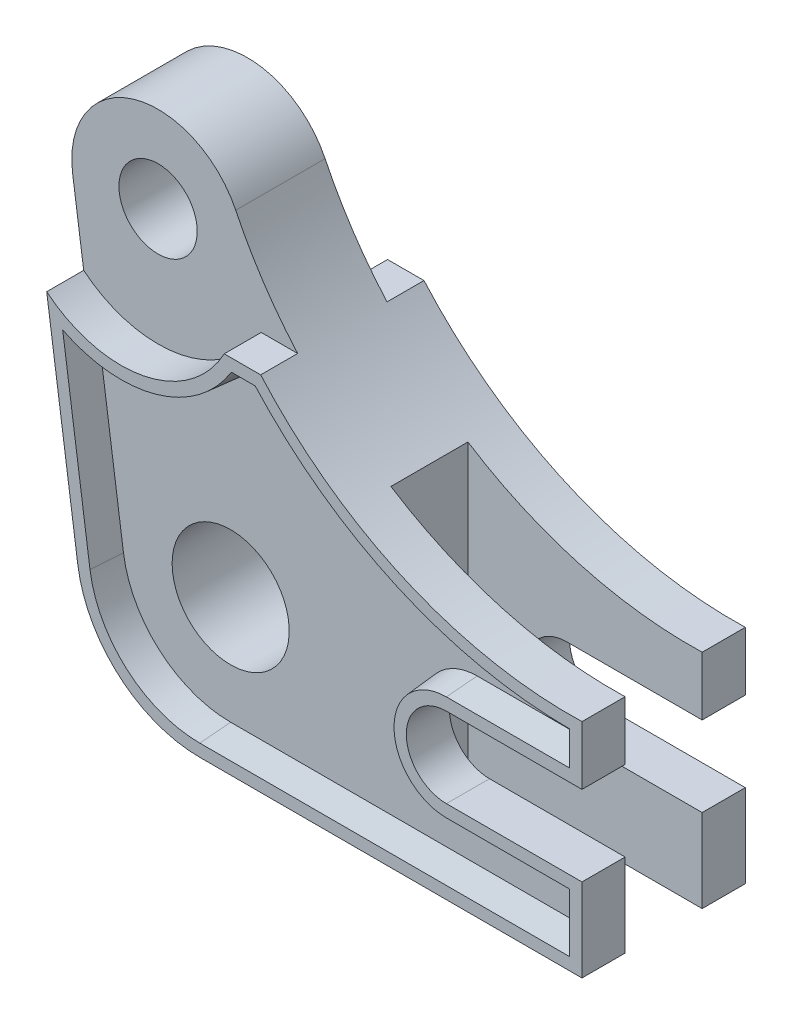
SolidWorks part; units mm, degrees
material "AISI 1020 Steel, Cold Rolled"
ref_plane "Front Plane" through (0, 0, 0) normal (0, 0, 1) x (1, 0, 0)
ref_plane "Top Plane" through (0, 0, 0) normal (0, 1, 0) x (1, 0, 0)
ref_plane "Right Plane" through (0, 0, 0) normal (1, 0, 0) x (0, 0, -1)
sketch "Sketch1" plane through (0, 0, 0) normal (0, 0, 1) x (1, 0, 0)
  line L0 (0, 0) -> (62, 0)
  line L1 (-19.8044, 17.21) -> (-26.64, 65.7309)
  line L2 (0, 20) -> (0, 45.9164) construction
  line L3 (0, 20) -> (-12.7769, 67.6839) construction
  line L4 (62, 0) -> (62, 36.0264)
  line L5 (40, 26.5) -> (62, 26.5)
  line L6 (40, 13.5) -> (62, 13.5)
  arc A0 (0, 0) -> (-19.8044, 17.21) centre (0, 20) cw
  arc A1 (-26.64, 65.7309) -> (-0.1776, 73.7879) centre (-12.7769, 67.6839) cw
  arc A2 (-0.1776, 73.7879) -> (62, 36.0264) centre (60.1188, 103) ccw
  circle A3 centre (0, 20) radius 9.5
  arc A4 (40, 26.5) -> (40, 13.5) centre (40, 20) ccw
  circle A5 centre (-12.7769, 67.6839) radius 6.35
  dimension "D2" = 20
  dimension "D4" = 14
  dimension "D8" = 19
  dimension "D9" = 13
  dimension "D12" = 12.7
  dimension "D6" = 134
  dimension "D1" = 62
  dimension "D3" = 49
  dimension "D5" = 15
  dimension "D10" = 22
  dimension "D11" = 20
  dimension "D7" = 103
extrude "Boss-Extrude1" add sketch "Sketch1" along normal blind 26.5 contours A4 L5 L4 A2 A1 L1 A0 L0 L6 A5 A3
sketch "Sketch2" plane through (0, 0, 0) normal (0, 1, 0) x (1, 0, 0)
  line L0 (62, -26.5) -> (62, 0) construction
  line L1 (24, -7) -> (62, -7)
  line L2 (24, -7) -> (24, -19.5)
  line L3 (24, -19.5) -> (62, -19.5)
  line L4 (62, -7) -> (62, -19.5)
  line L5 (62, 0) -> (-0.1776, 0) construction
  line L6 (-0.1776, -26.5) -> (62, -26.5) construction
  dimension "D1" = 7
  dimension "D2" = 7
  dimension "D3" = 38
extrude "Cut-Extrude1" cut sketch "Sketch2" along normal through all
sketch "Sketch3" plane through (0, 0, 26.5) normal (0, 0, 1) x (1, 0, 0)
  line L0 (3.9563, 58.6839) -> (9.8686, 58.6839)
  line L1 (-19.8044, 17.21) -> (-26.64, 65.7309) construction
  line L2 (-24.848, 53.0112) -> (-26.64, 65.7309)
  arc A0 (-24.848, 53.0112) -> (3.9563, 58.6839) centre (-12.7769, 67.6839) ccw
  arc A3 (-0.1776, 73.7879) -> (-26.64, 65.7309) centre (-12.7769, 67.6839) ccw construction
  arc A4 (-0.1776, 73.7879) -> (62, 36.0264) centre (60.1188, 103) ccw construction
  arc A5 (-0.1776, 73.7879) -> (9.8686, 58.6839) centre (60.1188, 103) ccw
  arc A6 (-0.1776, 73.7879) -> (-26.64, 65.7309) centre (-12.7769, 67.6839) ccw
  dimension "D1" = 38
  dimension "D2" = 9
extrude "Cut-Extrude3" cut sketch "Sketch3" against normal blind 6
sketch "Sketch6" plane through (0, 0, 0) normal (0, 0, -1) x (-1, 0, 0)
  line L0 (-9.8686, 58.6839) -> (-3.9563, 58.6839)
  line L1 (19.8044, 17.21) -> (26.64, 65.7309) construction
  line L2 (24.848, 53.0112) -> (26.64, 65.7309)
  arc A1 (-3.9563, 58.6839) -> (24.848, 53.0112) centre (12.7769, 67.6839) ccw
  circle A2 centre (12.7769, 67.6839) radius 6.35 construction
  circle A3 centre (12.7769, 67.6839) radius 6.35
  arc A4 (26.64, 65.7309) -> (0.1776, 73.7879) centre (12.7769, 67.6839) ccw construction
  arc A5 (-62, 36.0264) -> (0.1776, 73.7879) centre (-60.1188, 103) ccw construction
  arc A6 (26.64, 65.7309) -> (0.1776, 73.7879) centre (12.7769, 67.6839) ccw
  arc A7 (-9.8686, 58.6839) -> (0.1776, 73.7879) centre (-60.1188, 103) ccw
  dimension "D1" = 38
  dimension "D2" = 9
extrude "Cut-Extrude4" cut sketch "Sketch6" against normal blind 6
sketch "Sketch7" plane through (0, 0, 26.5) normal (0, 0, 1) x (1, 0, 0)
  line L21 (8.9737, 56.6839) -> (5.1117, 56.6839)
  line L22 (60, 28.5) -> (60, 34.0001)
  line L23 (40, 28.5) -> (60, 28.5)
  line L24 (60, 11.5) -> (40, 11.5)
  line L25 (60, 2) -> (60, 11.5)
  line L26 (0, 2) -> (60, 2)
  line L27 (-22.2554, 48.9447) -> (-17.824, 17.489)
  line L28 (9.8686, 58.6839) -> (3.9563, 58.6839)
  line L29 (-24.848, 53.0112) -> (-19.8044, 17.21)
  line L30 (0, 0) -> (62, 0)
  line L31 (62, 0) -> (62, 13.5)
  line L32 (62, 13.5) -> (40, 13.5)
  line L33 (40, 26.5) -> (62, 26.5)
  line L34 (62, 26.5) -> (62, 36.0264)
  line L35 (9.8686, 58.6839) -> (3.9563, 58.6839)
  line L36 (-24.848, 53.0112) -> (-19.8044, 17.21)
  line L37 (0, 0) -> (62, 0)
  line L38 (62, 0) -> (62, 13.5)
  line L39 (62, 13.5) -> (40, 13.5)
  line L40 (40, 26.5) -> (62, 26.5)
  line L41 (62, 26.5) -> (62, 36.0264)
  arc A12 (-22.2554, 48.9447) -> (5.1117, 56.6839) centre (-12.7769, 67.6839) ccw
  arc A13 (8.9737, 56.6839) -> (60, 34.0001) centre (60.1188, 103) ccw
  arc A14 (40, 28.5) -> (40, 11.5) centre (40, 20) ccw
  arc A15 (-17.824, 17.489) -> (0, 2) centre (0, 20) ccw
  arc A16 (-24.848, 53.0112) -> (3.9563, 58.6839) centre (-12.7769, 67.6839) ccw
  arc A17 (-19.8044, 17.21) -> (0, 0) centre (0, 20) ccw
  arc A18 (40, 26.5) -> (40, 13.5) centre (40, 20) ccw
  arc A19 (9.8686, 58.6839) -> (62, 36.0264) centre (60.1188, 103) ccw
  arc A20 (-24.848, 53.0112) -> (3.9563, 58.6839) centre (-12.7769, 67.6839) ccw
  arc A21 (-19.8044, 17.21) -> (0, 0) centre (0, 20) ccw
  arc A22 (40, 26.5) -> (40, 13.5) centre (40, 20) ccw
  arc A23 (9.8686, 58.6839) -> (62, 36.0264) centre (60.1188, 103) ccw
  dimension "D1" = 0
  dimension "D2" = 2
extrude "Cut-Extrude6" cut sketch "Sketch7" against normal offset from surface 2 draft 5 contours A12 L21 A13 L22 L23 A14 L24 L25 L26 A15 L27
sketch "Sketch8" plane through (0, 0, 0) normal (0, 0, -1) x (-1, 0, 0)
  line L0 (-5.1117, 56.6839) -> (-8.9737, 56.6839)
  line L1 (17.824, 17.489) -> (22.2554, 48.9447)
  line L2 (-60, 2) -> (0, 2)
  line L3 (-60, 11.5) -> (-60, 2)
  line L4 (-40, 11.5) -> (-60, 11.5)
  line L5 (-60, 28.5) -> (-40, 28.5)
  line L6 (-60, 34.0001) -> (-60, 28.5)
  line L7 (19.8044, 17.21) -> (24.848, 53.0112)
  line L8 (-3.9563, 58.6839) -> (-9.8686, 58.6839)
  line L9 (-62, 36.0264) -> (-62, 26.5)
  line L10 (-62, 26.5) -> (-40, 26.5)
  line L11 (-40, 13.5) -> (-62, 13.5)
  line L12 (-62, 13.5) -> (-62, 0)
  line L13 (-62, 0) -> (0, 0)
  line L14 (19.8044, 17.21) -> (24.848, 53.0112)
  line L15 (-3.9563, 58.6839) -> (-9.8686, 58.6839)
  line L16 (-62, 36.0264) -> (-62, 26.5)
  line L17 (-62, 26.5) -> (-40, 26.5)
  line L18 (-40, 13.5) -> (-62, 13.5)
  line L19 (-62, 13.5) -> (-62, 0)
  line L20 (-62, 0) -> (0, 0)
  arc A0 (-60, 34.0001) -> (-8.9737, 56.6839) centre (-60.1188, 103) ccw
  arc A1 (-5.1117, 56.6839) -> (22.2554, 48.9447) centre (12.7769, 67.6839) ccw
  arc A2 (0, 2) -> (17.824, 17.489) centre (0, 20) ccw
  arc A3 (-40, 11.5) -> (-40, 28.5) centre (-40, 20) ccw
  arc A4 (-3.9563, 58.6839) -> (24.848, 53.0112) centre (12.7769, 67.6839) ccw
  arc A5 (-62, 36.0264) -> (-9.8686, 58.6839) centre (-60.1188, 103) ccw
  arc A6 (-40, 13.5) -> (-40, 26.5) centre (-40, 20) ccw
  arc A7 (0, 0) -> (19.8044, 17.21) centre (0, 20) ccw
  arc A8 (-3.9563, 58.6839) -> (24.848, 53.0112) centre (12.7769, 67.6839) ccw
  arc A9 (-62, 36.0264) -> (-9.8686, 58.6839) centre (-60.1188, 103) ccw
  arc A10 (-40, 13.5) -> (-40, 26.5) centre (-40, 20) ccw
  arc A11 (0, 0) -> (19.8044, 17.21) centre (0, 20) ccw
  dimension "D1" = 0
  dimension "D2" = 2
extrude "Cut-Extrude7" cut sketch "Sketch8" against normal offset from surface 2 draft 5 contours A0 L0 A1 L1 A2 L2 L3 L4 A3 L5 L6
equation "\"A\"= 62"
equation "\"B\"= 20"
equation "\"C\"= 26.5"
equation "\"D1@Sketch1\"=\"A\""
equation "\"D2@Sketch1\"=\"B\""
equation "\"D11@Sketch1\"=\"B\""
equation "\"D1@Boss-Extrude1\"=\"C\""
